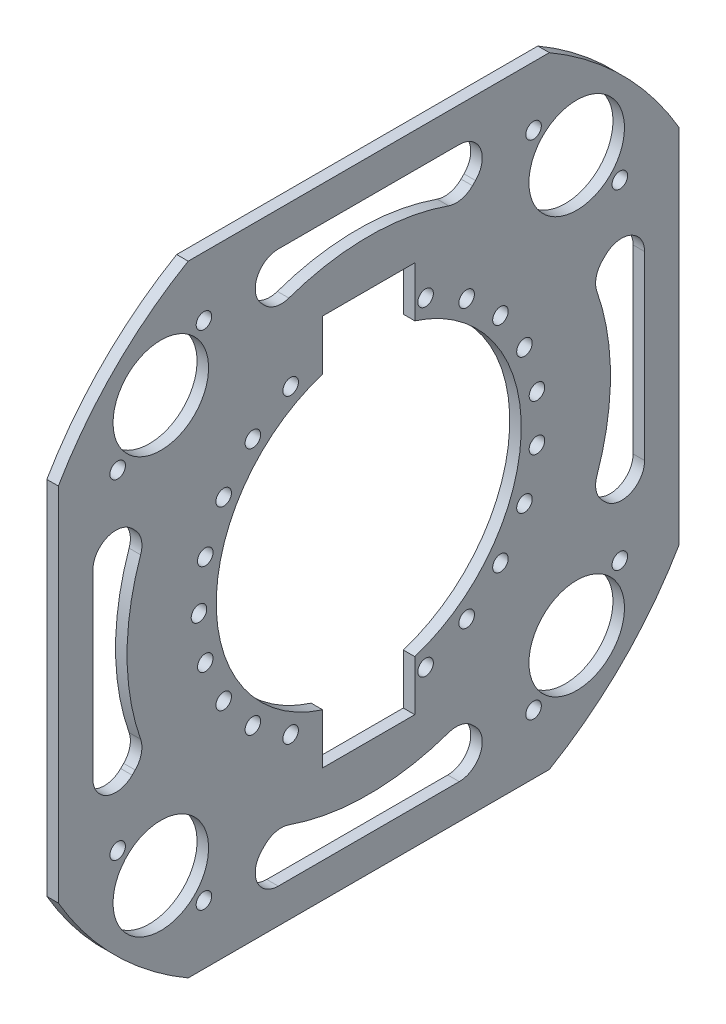
SolidWorks part; units mm, degrees
ref_plane "Plan de face" through (0, 0, 0) normal (0, 0, 1) x (1, 0, 0)
ref_plane "Plan de dessus" through (0, 0, 0) normal (0, 1, 0) x (1, 0, 0)
ref_plane "Plan de droite" through (0, 0, 0) normal (1, 0, 0) x (0, 0, -1)
sketch "Esquisse1" plane through (0, 0, 0) normal (1, 0, 0) x (0, 0, -1)
  line L0 (0, 0) -> (-210, 0) construction
  line L1 (0, 0) -> (0, -210) construction
  line L2 (40, -130) -> (40, -126.3181)
  line L3 (-40, -130) -> (40, -130) construction
  line L4 (-40, -130) -> (-40, -170)
  line L5 (-40, -170) -> (40, -170)
  line L6 (40, -130) -> (40, -170)
  line L7 (-40, -130) -> (-40, -126.3181)
  line L8 (40, 130) -> (40, 126.3181)
  line L9 (-40, 130) -> (-40, 126.3181)
  line L10 (-40, 130) -> (-40, 170)
  line L11 (-40, 130) -> (40, 130) construction
  line L12 (40, 130) -> (40, 170)
  line L13 (-40, 170) -> (40, 170)
  circle A0 centre (0, 0) radius 210
  circle A1 centre (0, 0) radius 147.5 construction
  circle A2 centre (-147.5, 0) radius 6.75
  arc A3 (40, -126.3181) -> (40, 126.3181) centre (0, 0) ccw
  circle A4 centre (-142.0303, 39.795) radius 6.75
  circle A5 centre (-126.0269, 76.6386) radius 6.75
  circle A6 centre (-100.6766, 107.7983) radius 6.75
  circle A7 centre (-67.8596, 130.9631) radius 6.75
  circle A8 centre (-30.0098, 144.4149) radius 6.75 construction
  circle A9 centre (10.0658, 147.1561) radius 6.75 construction
  circle A10 centre (49.3947, 138.9835) radius 6.75
  circle A11 centre (85.0603, 120.5031) radius 6.75
  circle A12 centre (114.4174, 93.0855) radius 6.75
  circle A13 centre (135.2887, 58.7642) radius 6.75
  circle A14 centre (146.1262, 20.0846) radius 6.75
  circle A15 centre (146.1262, -20.0846) radius 6.75
  circle A16 centre (135.2887, -58.7642) radius 6.75
  circle A17 centre (114.4174, -93.0855) radius 6.75
  circle A18 centre (85.0603, -120.5031) radius 6.75
  circle A19 centre (49.3947, -138.9835) radius 6.75
  circle A20 centre (10.0658, -147.1561) radius 6.75 construction
  circle A21 centre (-30.0098, -144.4149) radius 6.75 construction
  circle A22 centre (-67.8596, -130.9631) radius 6.75
  circle A23 centre (-100.6766, -107.7983) radius 6.75
  circle A24 centre (-126.0269, -76.6386) radius 6.75
  circle A25 centre (-142.0303, -39.795) radius 6.75
  arc A28 (-40, 126.3181) -> (-40, -126.3181) centre (0, 0) ccw
  point P55 (0, 0)
  point P59 (0, -130)
  point P60 (-130, 0)
  dimension "D1" = 147.5
  dimension "D2" = 13.5
  dimension "D3" = 265
  dimension "D5" = 420
  dimension "D6" = 40
  dimension "D9" = 132.5
  dimension "D7" = 80
  dimension "D8" = 130
  dimension "D4" = 23
extrude "Boss.-Extru.1" add sketch "Esquisse1" along normal blind 10
sketch "Esquisse2" plane through (0, 0, 0) normal (-1, 0, 0) x (0, 0, 1)
  line L0 (-180.6658, -180.6658) -> (-218.1424, -143.1891) construction
  line L1 (-180.6658, -180.6658) -> (-210.0107, -210.0107) construction
  line L2 (0, 0) -> (0, -255.5) construction
  line L3 (0, 0) -> (-180.6658, -180.6658) construction
  line L4 (-80.9762, -193.7598) -> (-127.4885, -240.2721)
  line L5 (240.2721, -127.4885) -> (269.6802, -156.8967)
  line L6 (-240.2721, -127.4885) -> (-193.7598, -80.9762)
  line L7 (-220.6173, -220.6173) -> (-210.0107, -210.0107) construction
  line L8 (-127.4885, 240.2721) -> (-80.9762, 193.7598)
  line L9 (240.2721, 127.4885) -> (269.6802, 156.8967)
  line L10 (-193.7598, 80.9762) -> (-240.2721, 127.4885)
  line L11 (240.2721, 127.4885) -> (193.7598, 80.9762)
  line L12 (127.4885, 240.2721) -> (156.8967, 269.6802)
  line L13 (80.9762, 193.7598) -> (127.4885, 240.2721)
  line L14 (127.4885, -240.2721) -> (80.3433, -193.1268)
  line L15 (127.4885, -240.2721) -> (156.8967, -269.6802)
  line L16 (193.7598, -80.9762) -> (240.2721, -127.4885)
  line L17 (-127.4885, 240.2721) -> (-156.8967, 269.6802)
  line L18 (-240.2721, 127.4885) -> (-269.6802, 156.8967)
  line L19 (-127.4885, -240.2721) -> (-156.8967, -269.6802)
  line L20 (-240.2721, -127.4885) -> (-269.6802, -156.8967)
  circle A0 centre (0, 0) radius 213 construction
  circle A1 centre (0, 0) radius 255.5 construction
  circle A2 centre (-180.6658, -180.6658) radius 42.5 construction
  circle A3 centre (-180.6658, -180.6658) radius 41.5
  circle A4 centre (-218.1424, -143.1891) radius 6.75
  circle A5 centre (-143.1891, -218.1424) radius 6.75
  circle A6 centre (0, 0) radius 210 construction
  arc A7 (-80.9762, -193.7598) -> (-193.7598, -80.9762) centre (0, 0) cw
  arc A8 (-193.7598, 80.9762) -> (-80.9762, 193.7598) centre (0, 0) cw
  circle A9 centre (-218.1424, 143.1891) radius 6.75
  circle A10 centre (-180.6658, 180.6658) radius 41.5
  circle A11 centre (-143.1891, 218.1424) radius 6.75
  arc A12 (80.9762, 193.7598) -> (193.7598, 80.9762) centre (0, 0) cw
  circle A13 centre (143.1891, 218.1424) radius 6.75
  circle A14 centre (180.6658, 180.6658) radius 41.5
  circle A15 centre (218.1424, 143.1891) radius 6.75
  arc A16 (193.7598, -80.9762) -> (80.9762, -193.7598) centre (0, 0) cw
  circle A17 centre (218.1424, -143.1891) radius 6.75
  circle A18 centre (180.6658, -180.6658) radius 41.5
  circle A19 centre (143.1891, -218.1424) radius 6.75
  circle A20 centre (0, 0) radius 312 construction
  arc A21 (240.2721, -127.4885) -> (240.2721, 127.4885) centre (0, 0) ccw construction
  arc A22 (-240.2721, 127.4885) -> (-240.2721, -127.4885) centre (0, 0) ccw construction
  arc A23 (127.4885, 240.2721) -> (-127.4885, 240.2721) centre (0, 0) ccw construction
  arc A24 (156.8967, -269.6802) -> (269.6802, -156.8967) centre (0, 0) ccw
  arc A25 (269.6802, 156.8967) -> (156.8967, 269.6802) centre (0, 0) ccw
  arc A26 (-127.4885, -240.2721) -> (127.4885, -240.2721) centre (0, 0) ccw construction
  arc A27 (-156.8967, 269.6802) -> (-269.6802, 156.8967) centre (0, 0) ccw
  arc A28 (-156.8967, -269.6802) -> (-269.6802, -156.8967) centre (0, 0) cw
  point P57 (0, 0)
  circle M11 centre (0, 0) radius 210
  dimension "D1" = 426
  dimension "D2" = 85
  dimension "D3" = 83
  dimension "D4" = 13.5
  dimension "D10" = 40
  dimension "D7" = 624
  dimension "D5" = 53
  dimension "D6" = 45
  dimension "D8" = 26.75
  dimension "D11" = 159.5
  dimension "D9" = 4
extrude "Boss.-Extru.2" add sketch "Esquisse2" against normal blind 10 contours A20 A26 L4 L6 A22 L10 L8 A23 L13 L11 A21 L16 L14 A17 A15 A14 A9 A3 A4 A5 A10 A11 A13 A18 A19 M11 | L9 A25 L12 L13 L11 A15 A14 A13 M11 | L17 A27 L18 L10 L8 A9 A10 A11 M11 | A28 L19 L4 L6 L20 A5 A4 A3 M11
sketch "Esquisse3" plane through (10, 0, 0) normal (1, 0, 0) x (0, 0, -1)
  line L0 (-156.8967, -269.6802) -> (156.8967, -269.6802)
  line L1 (156.8967, -269.6802) -> (126.8967, -239.6802)
  line L2 (-80.9762, -193.7598) -> (-156.8967, -269.6802) construction
  line L3 (126.8967, -239.6802) -> (-126.8967, -239.6802)
  line L4 (-193.7598, 80.9762) -> (-269.6802, 156.8967) construction
  line L5 (-126.8967, -239.6802) -> (-156.8967, -269.6802)
  line L6 (-269.6802, -156.8967) -> (-269.6802, 156.8967)
  line L7 (-269.6802, 156.8967) -> (-239.6802, 126.8967)
  line L8 (80.9762, 193.7598) -> (156.8967, 269.6802) construction
  line L9 (-239.6802, 126.8967) -> (-239.6802, -126.8967)
  line L11 (-239.6802, -126.8967) -> (-269.6802, -156.8967)
  line L12 (-156.8967, 269.6802) -> (156.8967, 269.6802)
  line L13 (156.8967, 269.6802) -> (126.8967, 239.6802)
  line L15 (126.8967, 239.6802) -> (-126.8967, 239.6802)
  line L17 (-126.8967, 239.6802) -> (-156.8967, 269.6802)
  line L18 (269.6802, 156.8967) -> (269.6802, -156.8967)
  line L19 (269.6802, -156.8967) -> (239.6802, -126.8967)
  line L21 (239.6802, -126.8967) -> (239.6802, 126.8967)
  line L23 (239.6802, 126.8967) -> (269.6802, 156.8967)
  line L24 (193.7598, 80.9762) -> (269.6802, 156.8967) construction
  dimension "D1" = 30
extrude "Boss.-Extru.3" add sketch "Esquisse3" against normal up to surface (10 mm away) up to face at (0, -76.6386, 119.2769)
fillet "Congé1" radius 20 16 edges at (5, 193.7598, -80.9762) (5, 80.9762, -193.7598) (5, -80.9762, -193.7598) (5, -193.7598, -80.9762) (5, -193.7598, 80.9762) (5, -80.9762, 193.7598) (5, 80.9762, 193.7598) (5, 193.7598, 80.9762) (5, -239.6802, 126.8967) (5, -239.6802, -126.8967) (5, -126.8967, -239.6802) (5, 126.8967, -239.6802) (5, 239.6802, -126.8967) (5, 239.6802, 126.8967) (5, 126.8967, 239.6802) (5, -126.8967, 239.6802)
